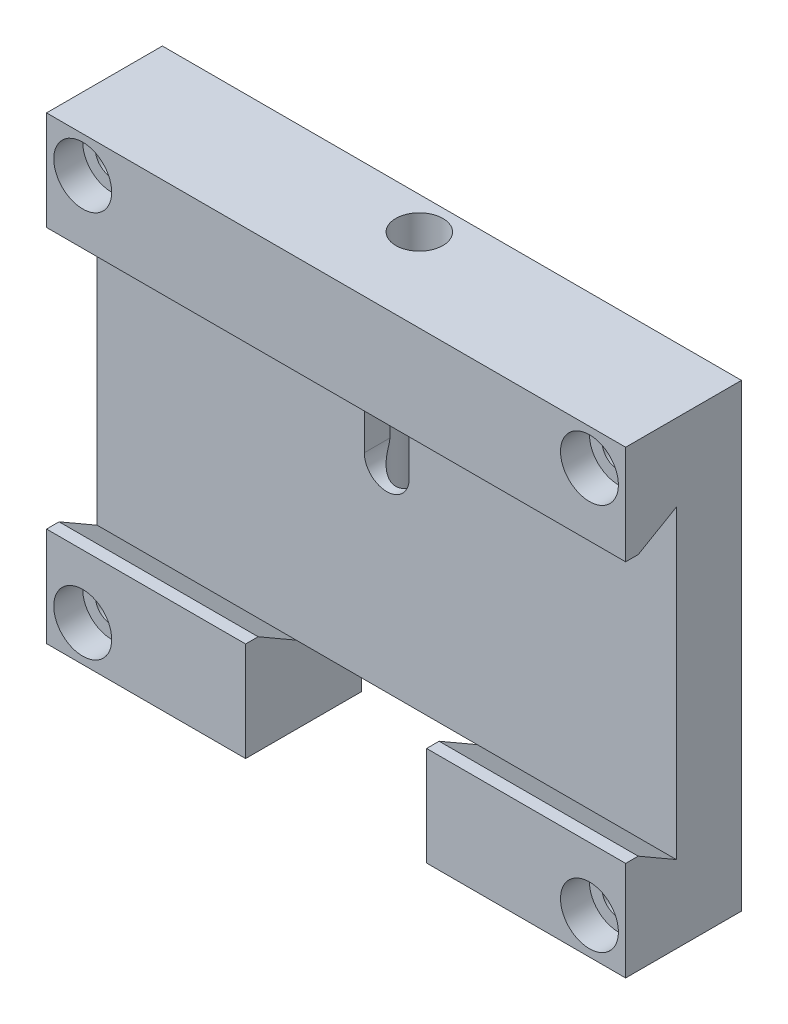
SolidWorks part; units mm, degrees
material "Сплав 2024"
ref_plane "Спереди" through (0, 0, 0) normal (0, 0, 1) x (1, 0, 0)
ref_plane "Сверху" through (0, 0, 0) normal (0, 1, 0) x (1, 0, 0)
ref_plane "Справа" through (0, 0, 0) normal (1, 0, 0) x (0, 0, -1)
sketch "Эскиз1" plane through (0, 0, 0) normal (0, 0, 1) x (1, 0, 0)
  line L1 (0, 0) -> (80, 0)
  line L2 (0, 0) -> (0, -63.5)
  line L3 (0, -63.5) -> (80, -63.5)
  line L4 (80, 0) -> (80, -63.5)
  dimension "D1" = 63.5
  dimension "D2" = 80
extrude "Бобышка-Вытянуть1" add sketch "Эскиз1" along normal blind 16
sketch "Эскиз2" plane through (0, 0, 0) normal (-1, 0, 0) x (0, 0, 1)
  line L0 (0, -31.75) -> (12.8711, -31.75) construction
  line L1 (0, 0) -> (0, -63.5) construction
  line L3 (16, 0) -> (16, -63.5) construction
  line L4 (9, -10.67) -> (16, -14.7115)
  line L5 (9, -10.67) -> (9, -52.83)
  line L6 (9, -52.83) -> (16, -48.7885)
  line L7 (16, -14.7115) -> (16, -48.7885)
  line L8 (9, -10.67) -> (16, -48.7885) construction
  line L9 (9, -52.83) -> (16, -14.7115) construction
  dimension "D1" = 42.16
  dimension "D2" = 60
  dimension "D3" = 60
  dimension "D4" = 7
extrude "Вырез-Вытянуть1" cut sketch "Эскиз2" against normal through all
ref_plane "Плоскость1" through (0, 0, 4) normal (0, 0, 1) x (1, 0, 0)
sketch "Эскиз3" plane through (0, 0, 4) normal (0, 0, 1) x (1, 0, 0)
  line L0 (0, -31.75) -> (80, -31.75) construction
  line L1 (0, -10.67) -> (0, -52.83) construction
  line L2 (80, -10.67) -> (80, -52.83) construction
  line L3 (40, 0) -> (40, -63.5) construction
  line L4 (80, 0) -> (0, 0) construction
  line L5 (0, -63.5) -> (80, -63.5) construction
  line L7 (40, -27.75) -> (80, -27.75)
  line L9 (40, -35.75) -> (80, -35.75)
  line L10 (80, -27.75) -> (80, -35.75)
  line L11 (40, -27.75) -> (80, -35.75) construction
  line L12 (40, -35.75) -> (80, -27.75) construction
  arc A0 (40, -27.75) -> (40, -35.75) centre (40, -31.75) ccw
  point P14 (60, -31.75)
  dimension "D1" = 8
sketch "Эскиз5" plane through (0, 0, 9) normal (0, 0, 1) x (1, 0, 0)
  line L0 (0, -31.75) -> (80, -31.75) construction
  line L1 (0, -31.75) -> (80, -31.75) construction
  line L2 (40, 0) -> (40, -63.5) construction
  line L3 (40, 0) -> (40, -63.5) construction
  line L4 (80, -10.67) -> (80, -52.83) construction
  line L5 (32, -27.75) -> (80, -27.75)
  line L7 (32, -35.75) -> (80, -35.75)
  line L8 (80, -27.75) -> (80, -35.75)
  line L9 (32, -27.75) -> (80, -35.75) construction
  line L10 (32, -35.75) -> (80, -27.75) construction
  arc A0 (32, -27.75) -> (32, -35.75) centre (32, -31.75) ccw
  point P6 (56, -31.75)
  dimension "D1" = 8
  dimension "D2" = 8
loft "Вырез-По сечениям1" [suppressed] cut profiles "Эскиз5", "Эскиз3"
sketch "Эскиз7" [suppressed] plane through (0, 0, 5) normal (0, 0, 1) x (1, 0, 0)
  line L0 (47.625, 0) -> (47.625, -63.5) construction
  line L1 (95.25, 0) -> (0, 0) construction
  line L2 (0, -63.5) -> (95.25, -63.5) construction
  line L3 (0, -31.75) -> (95.25, -31.75) construction
  line L4 (0, -13.2859) -> (0, -50.2141) construction
  line L5 (95.25, -35.75) -> (95.25, -27.75) construction
  line L6 (67.625, -24.8895) -> (67.625, -40.2612) construction
  line L7 (87.625, -24.8895) -> (87.625, -40.2612) construction
  line L8 (7.625, -24.8895) -> (7.625, -40.2612) construction
  line L9 (27.625, -24.8895) -> (27.625, -40.2612) construction
  circle A0 centre (27.625, -31.75) radius 4
  point P20 (27.625, -31.75)
  dimension "D3" = 8
  dimension "D1" = 20
  dimension "D2" = 20
extrude "Вырез-Вытянуть2" [suppressed] cut sketch "Эскиз7" along normal blind 5
hole_wizard "Отверстие обработанное метчиком M8x1.01" [suppressed] positions "Эскиз9" profile "Эскиз8" tap size "M8x1.0" standard "Ansi Metric"
sketch "Эскиз9" [suppressed] plane through (0, 0, 10) normal (0, 0, 1) x (1, 0, 0)
  line L0 (0, -31.75) -> (95.25, -31.75) construction
  line L1 (7.625, -24.8895) -> (7.625, -40.2612) construction
  line L2 (47.625, 0) -> (47.625, -63.5) construction
  line L3 (67.625, -24.8895) -> (67.625, -40.2612) construction
  line L4 (87.625, -24.8895) -> (87.625, -40.2612) construction
  point P0 (7.625, -31.75)
  point P2 (47.625, -31.75)
  point P4 (67.625, -31.75)
  point P6 (87.625, -31.75)
sketch "Эскиз8" plane through (7.625, -31.75, 10) normal (1, 0, 0) x (0, -1, 0)
  line L0 (0, 0) -> (0, 10)
  line L1 (0, 10) -> (3.5, 10)
  line L2 (3.5, 10) -> (3.5, 0)
  line L5 (3.5, 0) -> (0, 0)
  line L11 (0, -6.35) -> (0, 107.95) construction
  dimension "Диаметр проходного сверла" = 7
  dimension "Глубина проходного сверла" = 10
cosmetic thread "Отверстие резьбы1" [suppressed] parameters "D2"=8
cosmetic thread "Отверстие резьбы2" [suppressed] parameters "D2"=8
cosmetic thread "Отверстие резьбы3" [suppressed] parameters "D2"=8
cosmetic thread "Отверстие резьбы4" [suppressed] parameters "D2"=8
sketch "Эскиз10" [suppressed] plane through (0, 0, 10) normal (0, 0, 1) x (1, 0, 0)
  line L0 (90.25, -35.75) -> (95.25, -35.75)
  line L1 (95.25, -13.2859) -> (95.25, -27.75) construction
  line L2 (95.25, -27.75) -> (39.625, -27.75) construction
  line L3 (90.25, -27.75) -> (95.25, -27.75)
  line L4 (95.25, -27.75) -> (95.25, -22.75)
  line L5 (0, -31.75) -> (95.25, -31.75) construction
  line L6 (0, -31.75) -> (95.25, -31.75) construction
  line L7 (95.25, -35.75) -> (95.25, -40.75)
  arc A0 (90.25, -27.75) -> (95.25, -22.75) centre (90.25, -22.75) ccw
  arc A1 (90.25, -35.75) -> (95.25, -40.75) centre (90.25, -40.75) cw
  dimension "D1" = 5
  dimension "D2" = 5
extrude "Вырез-Вытянуть3" [suppressed] cut sketch "Эскиз10" against normal up to surface (5 mm away)
sketch "Эскиз11" plane through (0, 0, 0) normal (0, 0, -1) x (-1, 0, 0)
  line L0 (-80, -5) -> (0, -5) construction
  line L1 (-80, -63.5) -> (-80, 0) construction
  line L2 (0, 0) -> (0, -63.5) construction
  line L3 (-80, -58.5) -> (0, -58.5) construction
  line L4 (-80, 0) -> (0, 0) construction
  line L5 (0, -63.5) -> (-80, -63.5) construction
  line L8 (-80, -31.75) -> (0, -31.75) construction
  line L9 (-40, 0) -> (-40, -63.5) construction
  line L10 (-75, 0) -> (-75, -63.5) construction
  line L11 (-62.5, -11.75) -> (-17.5, -11.75) construction
  line L12 (-62.5, -11.75) -> (-62.5, -51.75) construction
  line L13 (-62.5, -51.75) -> (-17.5, -51.75) construction
  line L14 (-17.5, -11.75) -> (-17.5, -51.75) construction
  line L15 (-62.5, -11.75) -> (-17.5, -51.75) construction
  line L16 (-62.5, -51.75) -> (-17.5, -11.75) construction
  line L17 (-80, 0) -> (0, 0) construction
  line L18 (-80, -10.67) -> (-80, -52.83) construction
  line L19 (-5, 0) -> (-5, -63.5) construction
  line L20 (0, -10.67) -> (0, -52.83) construction
  line L21 (0, -63.5) -> (-80, -63.5) construction
  point P20 (-40, -31.75)
  dimension "D1" = 5
  dimension "D2" = 5
  dimension "D3" = 5
  dimension "D4" = 5
  dimension "D5" = 45
  dimension "D6" = 40
hole_wizard "Отверстие обработанное метчиком M4x0.71" [suppressed] positions "Эскиз13" profile "Эскиз12" tap size "M4x0.7" standard "Ansi Metric"
sketch "Эскиз13" plane through (0, 0, 0) normal (0, 0, -1) x (-1, 0, 0)
  line L0 (-80, -7) -> (0, -7) construction
  line L1 (-65, 0) -> (-65, -63.5) construction
  line L2 (-15, 0) -> (-15, -63.5) construction
  line L3 (-80, -56.5) -> (0, -56.5) construction
  point P0 (-65, -7)
  point P6 (-15, -7)
  point P10 (-15, -56.5)
  point P14 (-65, -56.5)
sketch "Эскиз12" plane through (65, -7, 0) normal (1, 0, 0) x (0, 1, 0)
  line L0 (0, 0) -> (0, 16)
  line L1 (0, 16) -> (1.65, 16)
  line L2 (1.65, 16) -> (1.65, 0)
  line L5 (1.65, 0) -> (0, 0)
  line L11 (0, -6.35) -> (0, 107.95) construction
  dimension "Диаметр проходного сверла" = 3.3
  dimension "Глубина проходного сверла" = 16
cosmetic thread "Отверстие резьбы5" [suppressed] parameters "D2"=4
cosmetic thread "Отверстие резьбы6" [suppressed] parameters "D2"=4
cosmetic thread "Отверстие резьбы7" [suppressed] parameters "D2"=4
cosmetic thread "Отверстие резьбы8" [suppressed] parameters "D2"=4
sketch "Эскиз15" plane through (0, 0, 16) normal (0, 0, 1) x (1, 0, 0)
  line L0 (40, 0) -> (40, -63.5) construction
  line L1 (80, 0) -> (0, 0) construction
  line L2 (0, -63.5) -> (80, -63.5) construction
  line L3 (80, -48.7885) -> (0, -48.7885) construction
  line L4 (27.5, -48.7885) -> (52.5, -48.7885)
  line L5 (27.5, -48.7885) -> (27.5, -63.5)
  line L6 (27.5, -63.5) -> (52.5, -63.5)
  line L7 (52.5, -48.7885) -> (52.5, -63.5)
  line L8 (27.5, -48.7885) -> (52.5, -63.5) construction
  line L9 (27.5, -63.5) -> (52.5, -48.7885) construction
  point P6 (40, -56.1443)
  dimension "D1" = 25
extrude "Вырез-Вытянуть4" cut sketch "Эскиз15" against normal up to surface (7 mm away) up to face at (40, -31.75, 9)
sketch "Эскиз16" plane through (0, 0, 9) normal (0, 0, 1) x (1, 0, 0)
  line L0 (40, 0) -> (40, -63.5) construction
  line L1 (27.5, -52.83) -> (52.5, -52.83)
  line L2 (27.5, -52.83) -> (27.5, -63.5)
  line L3 (27.5, -63.5) -> (52.5, -63.5)
  line L4 (52.5, -52.83) -> (52.5, -63.5)
  line L5 (27.5, -52.83) -> (52.5, -63.5) construction
  line L6 (27.5, -63.5) -> (52.5, -52.83) construction
  line L7 (27.5, -63.5) -> (52.5, -63.5) construction
  line L8 (80, -52.83) -> (52.5, -52.83) construction
  line L9 (52.5, -63.5) -> (52.5, -52.83) construction
  point P0 (40, -58.165)
extrude "Вырез-Вытянуть5" cut sketch "Эскиз16" against normal up to surface (9 mm away) up to face at (40, -31.75, 0)
sketch "Эскиз17" plane through (0, -52.83, 0) normal (0, -1, 0) x (1, 0, 0)
  line L0 (35.125, 5) -> (60.125, 5) construction
  line L3 (40, 9) -> (40, 0) construction
  line L4 (80, 9) -> (0, 9) construction
  line L5 (27.5, 0) -> (52.5, 0) construction
  circle A0 centre (32.5, 5) radius 2.5
  circle A1 centre (47.5, 5) radius 2.5
  dimension "D1" = 5
  dimension "D2" = 7.5
  dimension "D3" = 5
extrude "Вырез-Вытянуть6" cut sketch "Эскиз17" against normal blind 4
hole_wizard "Отверстие обработанное метчиком M4x0.72" positions "Эскиз19" profile "Эскиз18" tap size "M4x0.7" standard "Ansi Metric"
sketch "Эскиз19" plane through (0, -52.83, 0) normal (0, -1, 0) x (-1, 0, 0)
  line L0 (-40, -9) -> (-40, 0) construction
  line L1 (-35.125, -5) -> (-60.125, -5) construction
  point P0 (-40, -5)
sketch "Эскиз18" plane through (40, -52.83, 5) normal (1, 0, 0) x (0, 0, -1)
  line L0 (0, 0) -> (0, 10.9914)
  line L1 (0, 10.9914) -> (1.65, 10)
  line L2 (1.65, 10) -> (1.65, 0)
  line L5 (1.65, 0) -> (0, 0)
  line L10 (0, 10.9914) -> (-1.65, 10) construction
  line L11 (0, -6.35) -> (0, 107.95) construction
  dimension "Диаметр сверла" = 3.3
  dimension "Глубина сверла" = 10
  dimension "Угол заточки сверла" = 118
cosmetic thread "Отверстие резьбы9" parameters "D1"=8, "D2"=4
hole_wizard "Отверстие обработанное метчиком 3/8-161" [suppressed] positions "Эскиз21" profile "Эскиз20" tap size "3/8-16" standard "Ansi Inch"
sketch "Эскиз21" plane through (0, 0, 0) normal (0, 0, -1) x (-1, 0, 0)
  point P0 (-70.125, -11.75)
  point P3 (-70.125, -51.75)
  point P6 (-25.125, -51.75)
  point P9 (-25.125, -11.75)
sketch "Эскиз20" plane through (70.125, -11.75, 0) normal (1, 0, 0) x (0, 1, 0)
  line L0 (0, 0) -> (0, 10.3847)
  line L1 (0, 10.3847) -> (3.9687, 8)
  line L2 (3.9687, 8) -> (3.9687, 0)
  line L5 (3.9687, 0) -> (0, 0)
  line L10 (0, 10.3847) -> (-3.9688, 8) construction
  line L11 (0, -6.35) -> (0, 107.95) construction
  dimension "Диаметр сверла" = 7.9375
  dimension "Глубина сверла" = 8
  dimension "Угол заточки сверла" = 118
cosmetic thread "Отверстие резьбы10" [suppressed] parameters "D1"=8, "D2"=9.525
cosmetic thread "Отверстие резьбы11" [suppressed] parameters "D1"=8, "D2"=9.525
cosmetic thread "Отверстие резьбы12" [suppressed] parameters "D1"=8, "D2"=9.525
cosmetic thread "Отверстие резьбы13" [suppressed] parameters "D1"=8, "D2"=9.525
chamfer "Фаска1" [suppressed] distance 4 angle 45
hole_wizard "Отверстие обработанное метчиком 1/4-201" [suppressed] positions "Эскиз23" profile "Эскиз22" tap size "1/4-20" standard "Ansi Inch"
sketch "Эскиз23" plane through (0, 0, 0) normal (0, 0, -1) x (-1, 0, 0)
  point P0 (-25.125, -51.75)
  point P3 (-25.125, -11.75)
  point P6 (-70.125, -11.75)
  point P9 (-70.125, -51.75)
sketch "Эскиз22" plane through (25.125, -51.75, 0) normal (1, 0, 0) x (0, 1, 0)
  line L0 (0, 0) -> (0, 10.5338)
  line L1 (0, 10.5338) -> (2.5527, 9)
  line L2 (2.5527, 9) -> (2.5527, 0)
  line L5 (2.5527, 0) -> (0, 0)
  line L10 (0, 10.5338) -> (-2.5527, 9) construction
  line L11 (0, -6.35) -> (0, 107.95) construction
  dimension "Диаметр сверла" = 5.1054
  dimension "Глубина сверла" = 9
  dimension "Угол заточки сверла" = 118
cosmetic thread "Отверстие резьбы14" [suppressed] parameters "D1"=9, "D2"=6.35
cosmetic thread "Отверстие резьбы15" [suppressed] parameters "D1"=9, "D2"=6.35
cosmetic thread "Отверстие резьбы16" [suppressed] parameters "D1"=9, "D2"=6.35
cosmetic thread "Отверстие резьбы17" [suppressed] parameters "D1"=9, "D2"=6.35
sketch "Эскиз25" plane through (0, 0, 9) normal (0, 0, 1) x (1, 0, 0)
  line L0 (40, 0) -> (40, -52.83) construction
  line L1 (80, 0) -> (0, 0) construction
  line L2 (52.5, -52.83) -> (27.5, -52.83) construction
  line L3 (40, -18.7115) -> (40, -25.7115) construction
  line L4 (43.1, -18.7115) -> (43.1, -25.7115)
  line L5 (36.9, -18.7115) -> (36.9, -25.7115)
  line L6 (80, -14.7115) -> (0, -14.7115) construction
  arc A0 (43.1, -18.7115) -> (36.9, -18.7115) centre (40, -18.7115) ccw
  arc A1 (36.9, -25.7115) -> (43.1, -25.7115) centre (40, -25.7115) ccw
  point P8 (40, -22.2115)
  dimension "D1" = 3.1
  dimension "D2" = 4
  dimension "D3" = 7
extrude "Вырез-Вытянуть7" cut sketch "Эскиз25" against normal blind 4
sketch "Эскиз26" plane through (0, 0, 0) normal (0, 1, 0) x (1, 0, 0)
  line L0 (0, -9) -> (80, -9) construction
  line L1 (0, -16) -> (0, 0) construction
  line L2 (80, -16) -> (80, 0) construction
  line L4 (80, 0) -> (0, 0) construction
  line L5 (40, 0) -> (40, -16) construction
  line L6 (80, -16) -> (0, -16) construction
  circle A0 centre (40, -4.5) radius 3.25
  dimension "D2" = 6.5
  dimension "D1" = 9
  dimension "D3" = 4.5
extrude "Вырез-Вытянуть8" cut sketch "Эскиз26" against normal blind 38
sketch "Эскиз27" plane through (0, 0, 0) normal (0, 0, -1) x (-1, 0, 0)
  line L0 (-80, 0) -> (0, 0) construction
  line L1 (-80, 0) -> (-70, 0)
  line L2 (-80, 0) -> (-80, -63.5)
  line L3 (-80, -63.5) -> (-70, -63.5)
  line L4 (-70, 0) -> (-70, -63.5)
  line L5 (-52.5, -63.5) -> (-80, -63.5) construction
  line L7 (-40, 0) -> (-40, -63.5) construction
  line L8 (-80, -63.5) -> (-80, 0) construction
  line L9 (0, -63.5) -> (-10, -63.5)
  line L10 (0, 0) -> (0, -63.5)
  line L11 (0, 0) -> (-10, 0)
  line L12 (-10, 0) -> (-10, -63.5)
  dimension "D1" = 10
extrude "Вырез-Вытянуть9" [suppressed] cut sketch "Эскиз27" against normal blind 5
hole_wizard "Цековка для винта с внутренним шестигранником M41" positions "Эскиз29" profile "Эскиз28" counterbore size "M4" standard "Ansi Metric" end condition through all
sketch "Эскиз29" plane through (30.7592, 26.7934, 16) normal (0, 0, -1) x (-1, 0, 0)
  line L0 (-49.2408, -31.7934) -> (30.7592, -31.7934) construction
  line L1 (-44.2408, -26.7934) -> (-44.2408, -90.2934) construction
  line L2 (-49.2408, -85.2934) -> (30.7592, -85.2934) construction
  line L3 (25.7592, -26.7934) -> (25.7592, -90.2934) construction
  point P0 (-44.2408, -31.7934)
  point P6 (-44.2408, -85.2934)
  point P10 (25.7592, -85.2934)
  point P14 (25.7592, -31.7934)
sketch "Эскиз28" plane through (75, -5, 16) normal (1, 0, 0) x (0, -1, 0)
  line L0 (0, 0) -> (0, 16)
  line L1 (0, 16) -> (2.25, 16)
  line L3 (2.25, 16) -> (2.25, 4)
  line L4 (2.25, 4) -> (4, 4)
  line L5 (4, 4) -> (4, 0)
  line L7 (4, 0) -> (0, 0)
  line L11 (0, -6.35) -> (0, 107.95) construction
  dimension "Диаметр сквозного отверстия" = 4.5
  dimension "Глубина сквозного отверстия" = 16
  dimension "Диаметр цековки" = 8
  dimension "Глубина цековки" = 4
chamfer "Фаска2" distance 1 angle 90 3 edges at (66.25, -48.7885, 16) (13.75, -48.7885, 16) (40, -14.7115, 16)
